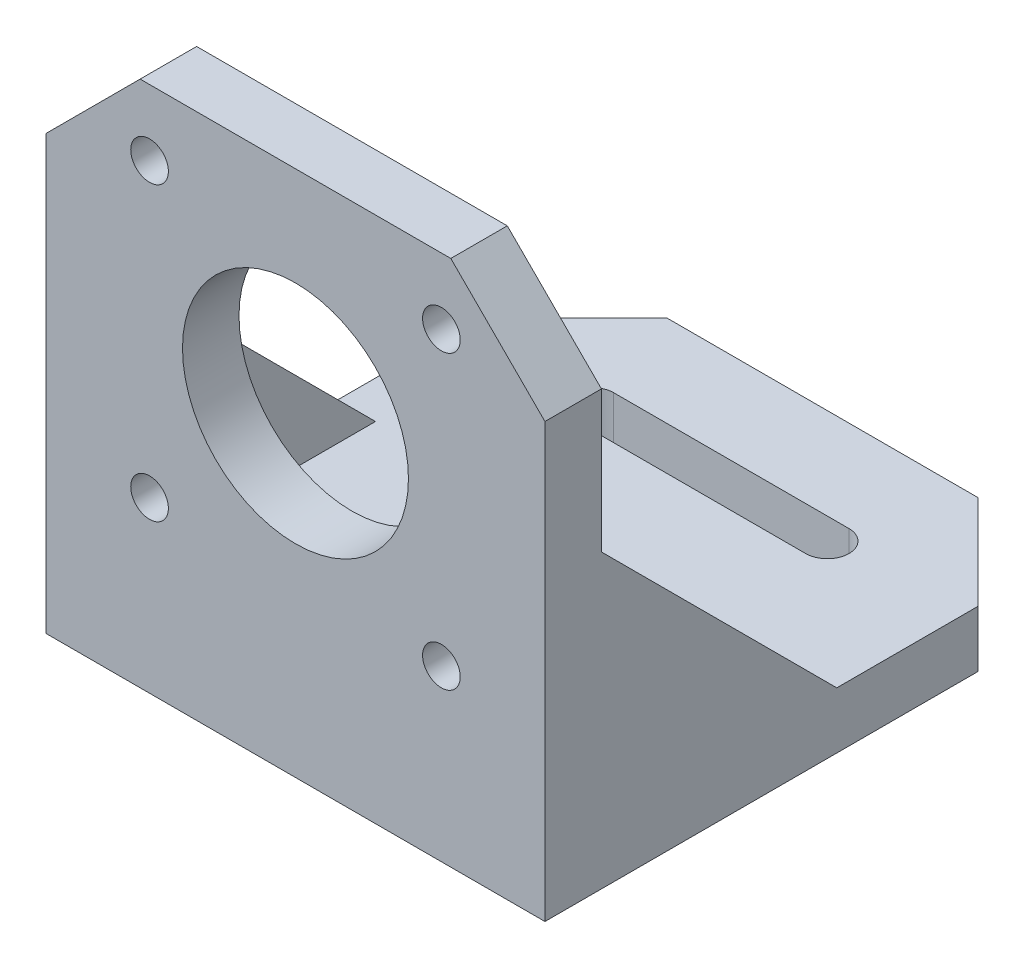
SolidWorks part; units mm, degrees
ref_plane "Спереди" through (0, 0, 0) normal (0, 0, 1) x (1, 0, 0)
ref_plane "Сверху" through (0, 0, 0) normal (0, 1, 0) x (1, 0, 0)
ref_plane "Справа" through (0, 0, 0) normal (1, 0, 0) x (0, 0, -1)
sketch "Эскиз1" plane through (0, 0, 0) normal (1, 0, 0) x (0, 0, -1)
  line L0 (0, 0) -> (0, 56)
  line L1 (0, 56) -> (6, 56)
  line L2 (6, 56) -> (6, 6)
  line L3 (6, 6) -> (56, 6)
  line L4 (56, 6) -> (56, 0)
  line L5 (56, 0) -> (0, 0)
  dimension "D1" = 50
  dimension "D2" = 50
  dimension "D3" = 6
  dimension "D4" = 6
extrude "Бобышка-Вытянуть1" add sketch "Эскиз1" along normal blind 53
sketch "Эскиз2" plane through (53, 0, 0) normal (1, 0, 0) x (0, 0, -1)
  line L0 (6, 31) -> (31, 6)
  line L1 (6, 6) -> (6, 56) construction
  line L2 (56, 6) -> (6, 6) construction
  line L3 (31, 6) -> (6, 6)
  line L4 (6, 6) -> (6, 31)
extrude "Бобышка-Вытянуть2" add sketch "Эскиз2" against normal blind 4
sketch "Эскиз3" plane through (0, 0, 0) normal (-1, 0, 0) x (0, 0, 1)
  line L0 (-6, 31) -> (-6, 6)
  line L1 (-6, 6) -> (-6, 56) construction
  line L2 (-6, 6) -> (-31, 6)
  line L3 (-56, 6) -> (-6, 6) construction
  line L4 (-31, 6) -> (-6, 31)
extrude "Бобышка-Вытянуть3" add sketch "Эскиз3" against normal blind 4 separate body
sketch "Эскиз4" plane through (0, 0, 0) normal (0, 0, 1) x (1, 0, 0)
  line L0 (0, 60) -> (53, 7) construction
  line L1 (53, 56) -> (53, 0) construction
  line L2 (53, 7) -> (0, 7) construction
  line L3 (0, 56) -> (0, 0) construction
  line L4 (0, 7) -> (53, 60) construction
  line L5 (11, 49) -> (42, 49) construction
  line L6 (42, 49) -> (42, 18) construction
  line L7 (42, 18) -> (11, 18) construction
  line L8 (11, 18) -> (11, 49) construction
  line L10 (53, 0) -> (0, 0) construction
  circle A0 centre (11, 49) radius 2
  circle A1 centre (42, 49) radius 2
  circle A2 centre (42, 18) radius 2
  circle A3 centre (11, 18) radius 2
  circle A4 centre (26.5, 33.5) radius 12
  dimension "D2" = 4
  dimension "D3" = 24
  dimension "D1" = 31
  dimension "D4" = 90
  dimension "D5" = 7
extrude "Вырез-Вытянуть1" cut sketch "Эскиз4" against normal through all and the other way through all
chamfer "Фаска1" distance 10 angle 45 2 edges at (53, 56, -3) (0, 56, -3)
sketch "Эскиз5" plane through (0, 6, 0) normal (0, 1, 0) x (1, 0, 0)
  line L0 (44, 14) -> (9, 14) construction
  line L1 (44, 11.7) -> (9, 11.7)
  line L2 (44, 16.3) -> (9, 16.3)
  line L3 (39, 44) -> (14, 44) construction
  line L4 (39, 41.7) -> (14, 41.7)
  line L5 (39, 46.3) -> (14, 46.3)
  line L6 (26.5, 56) -> (26.5, 6) construction
  line L7 (53, 56) -> (0, 56) construction
  line L8 (49, 6) -> (0, 6) construction
  line L9 (43, 0) -> (10, 0) construction
  arc A0 (44, 11.7) -> (44, 16.3) centre (44, 14) ccw
  arc A1 (9, 16.3) -> (9, 11.7) centre (9, 14) ccw
  arc A2 (39, 41.7) -> (39, 46.3) centre (39, 44) ccw
  arc A3 (14, 46.3) -> (14, 41.7) centre (14, 44) ccw
  point P2 (26.5, 14)
  point P7 (26.5, 44)
  dimension "D1" = 25
  dimension "D2" = 35
  dimension "D3" = 14
  dimension "D4" = 30
  dimension "D5" = 4.6
  dimension "D6" = 4.6
extrude "Вырез-Вытянуть2" cut sketch "Эскиз5" against normal through all
chamfer "Фаска2" distance 10 angle 45 2 edges at (0, 3, -56) (53, 3, -56)
fillet "Скругление1" radius 3 1 edges at (24.5, 6, -6)
